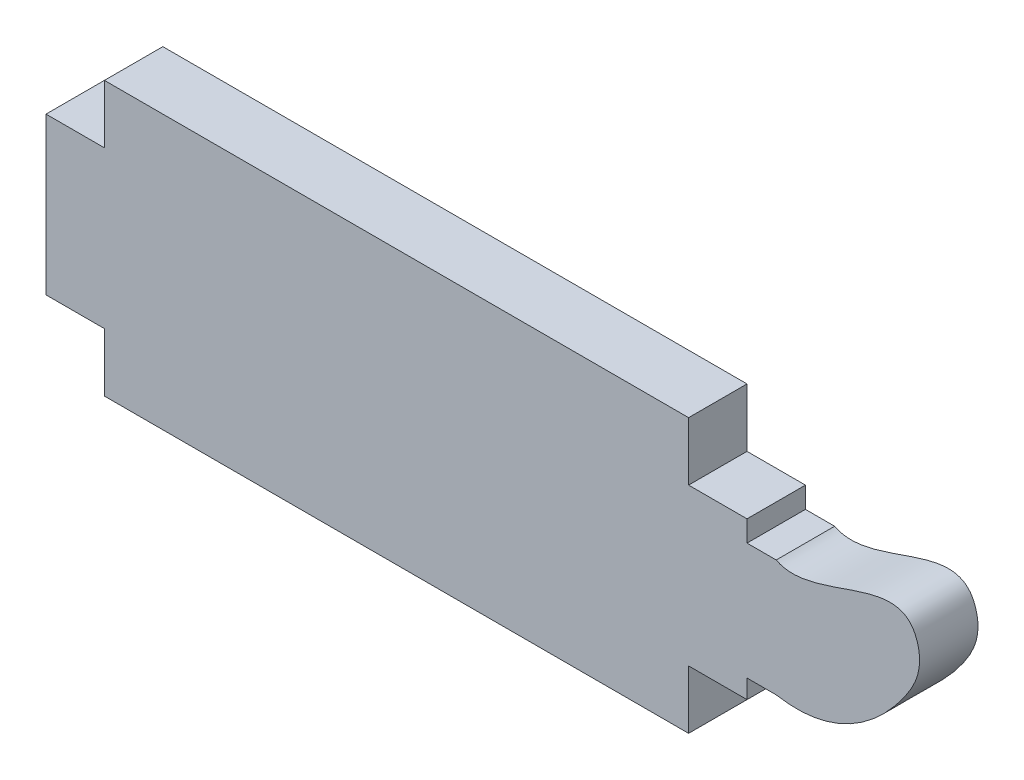
SolidWorks part; units mm, degrees
ref_plane "Front Plane" through (0, 0, 0) normal (0, 0, 1) x (1, 0, 0)
ref_plane "Top Plane" through (0, 0, 0) normal (0, 1, 0) x (1, 0, 0)
ref_plane "Right Plane" through (0, 0, 0) normal (1, 0, 0) x (0, 0, -1)
sketch "Sketch1" plane through (0, 0, 0) normal (0, 0, 1) x (1, 0, 0)
  line L0 (0, 5.6397) -> (0, 8.8147) construction
  line L1 (0, 5.6397) -> (-31.75, 5.6397)
  line L2 (3.175, 8.8147) -> (3.175, 9.8321)
  line L3 (0, 20.5001) -> (-31.75, 20.5001)
  line L4 (-34.925, 8.8147) -> (-34.925, 17.3251)
  line L5 (3.175, 16.1821) -> (3.175, 17.3251)
  line L7 (3.175, 17.3251) -> (0, 17.3251)
  line L8 (0, 20.5001) -> (0, 17.3251)
  line L9 (-31.75, 5.6397) -> (-31.75, 8.8147) construction
  line L12 (3.175, 8.8147) -> (0, 8.8147)
  line L13 (0, 5.6397) -> (0, 8.8147)
  line L14 (-34.925, 17.3251) -> (-31.75, 17.3251)
  line L17 (-31.75, 17.3251) -> (-31.75, 20.5001)
  line L20 (-34.925, 8.8147) -> (-31.75, 8.8147)
  line L21 (-31.75, 5.6397) -> (-31.75, 8.8147)
  line L24 (3.175, 9.8321) -> (4.7625, 9.8321)
  line L26 (3.175, 16.1821) -> (4.7625, 16.1821)
  spline S0 degree 3 poles (4.7625, 9.8321) (7.6598, 9.3171) (10.7283, 11.3427) (12.8261, 14.9457) (11.5758, 19.1589) (6.7186, 15.1667) (4.7625, 16.1821) knots 0 0 0 0 0.407369 0.542633 0.615483 1 1 1 1
  dimension "D1" = 3.175
  dimension "D2" = 3.175
  dimension "D3" = 3.175
  dimension "D4" = 3.175
  dimension "D5" = 1.5875
  dimension "D6" = 6.35
  dimension "D7" = 4.318
extrude "Boss-Extrude1" add sketch "Sketch1" against normal blind 3.175 contours S0 L26 L5 L7 L8 L3 L17 L14 L4 L20 L21 L1 L13 L12 L2 L24
